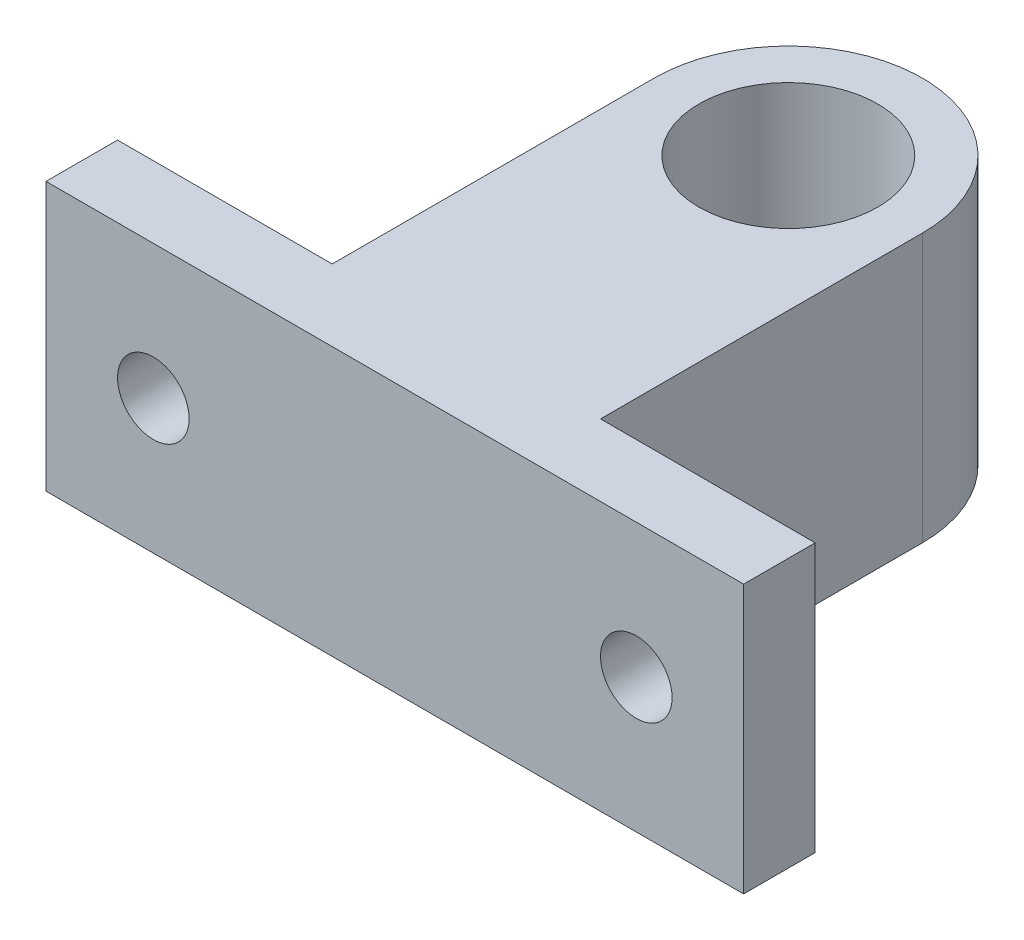
SolidWorks part; units mm, degrees
ref_plane "Plan de face" through (0, 0, 0) normal (0, 0, 1) x (1, 0, 0)
ref_plane "Plan de dessus" through (0, 0, 0) normal (0, 1, 0) x (1, 0, 0)
ref_plane "Plan de droite" through (0, 0, 0) normal (1, 0, 0) x (0, 0, -1)
sketch "Esquisse1" plane through (0, 0, 0) normal (0, 1, 0) x (1, 0, 0)
  line L1 (0, 0) -> (20, 0)
  line L2 (0, 0) -> (0, 30)
  line L3 (0, 30) -> (20, 30)
  line L4 (20, 0) -> (20, 30)
  line L5 (2.5, 22) -> (17.5, 22)
  line L6 (2.5, 22) -> (2.5, 0)
  line L7 (2.5, 0) -> (17.5, 0)
  line L8 (17.5, 22) -> (17.5, 0)
  circle A0 centre (10, 22) radius 5
  circle A1 centre (10, 22) radius 7.5
  dimension "D4" = 10
  dimension "D1" = 10
  dimension "D2" = 22
  dimension "D3" = 30
extrude "Boss.-Extru.1" add sketch "Esquisse1" along normal blind 15 contours L5 A1 A0 | L5 A1 A0 | A1 L6 L1 L8
sketch "Esquisse2" plane through (17.5, 0, 0) normal (1, 0, 0) x (0, 0, -1)
  line L0 (22, 0) -> (0, 0) construction
  line L1 (0, 15) -> (4, 15)
  line L2 (0, 15) -> (0, 0)
  line L3 (0, 0) -> (4, 0)
  line L4 (4, 15) -> (4, 0)
  dimension "D1" = 4
extrude "Boss.-Extru.2" add sketch "Esquisse2" along normal blind 12 and the other way blind 27
sketch "Esquisse3" plane through (0, 0, 0) normal (0, 0, 1) x (1, 0, 0)
  line L0 (-9.5, 15) -> (-9.5, 0) construction
  line L1 (29.5, 15) -> (29.5, 0) construction
  line L2 (-9.5, 0) -> (29.5, 0) construction
  circle A0 centre (-3.5, 7.5) radius 2
  circle A1 centre (23.5, 7.5) radius 2
  dimension "D2" = 4
  dimension "D3" = 4
  dimension "D1" = 6
  dimension "D4" = 6
  dimension "D5" = 7.5
  dimension "D6" = 7.5
extrude "Enlèv. mat.-Extru.1" cut sketch "Esquisse3" against normal blind 12
